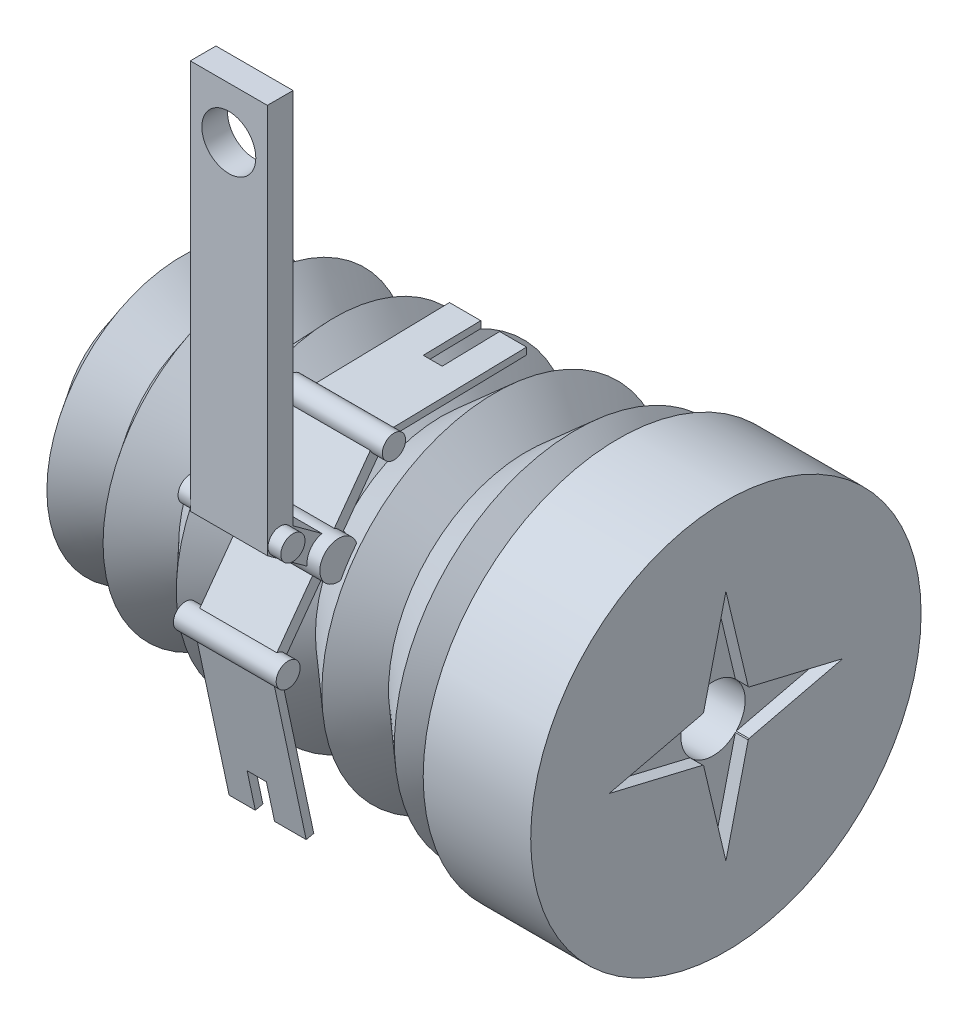
SolidWorks part; units mm, degrees
ref_plane "Ebene vorne" through (0, 0, 0) normal (0, 0, 1) x (1, 0, 0)
ref_plane "Ebene oben" through (0, 0, 0) normal (0, 1, 0) x (1, 0, 0)
ref_plane "Ebene rechts" through (0, 0, 0) normal (1, 0, 0) x (0, 0, -1)
sketch "Skizze2" plane through (0, 0, 0) normal (0, 0, 1) x (1, 0, 0)
  line L0 (0, 0) -> (40, 0) construction
  line L1 (0, 0) -> (0, 6)
  line L2 (40, 0) -> (0, 0)
  line L3 (0, 6) -> (3.3665, 10.5283)
  line L4 (3.3665, 10.5283) -> (6.4121, 8.2642)
  line L5 (6.4121, 8.2642) -> (9.1304, 11.9207)
  line L6 (9.1304, 11.9207) -> (12.157, 9.0646)
  line L7 (12.157, 9.0646) -> (15.1906, 12.2794)
  line L8 (15.1906, 12.2794) -> (17.3749, 9.8003)
  line L9 (17.3749, 9.8003) -> (20.8454, 12.8582)
  line L10 (20.8454, 12.8582) -> (23.5398, 9.8003)
  line L11 (23.5398, 9.8003) -> (27.7236, 13.4867)
  line L12 (27.7236, 13.4867) -> (30.1561, 10.726)
  line L13 (30.1561, 10.726) -> (34.0133, 14.1246)
  line L14 (34.0133, 14.1246) -> (36.4763, 11.3293)
  line L15 (36.4763, 11.3293) -> (37.3235, 15.1947)
  line L16 (37.3235, 15.1947) -> (45.6933, 15.1947)
  line L17 (45.6933, 15.1947) -> (45.6933, 0)
  line L18 (45.6933, 0) -> (40, 0)
  dimension "D1" = 40
  dimension "D2" = 12
revolve "Rotation5" add sketch "Skizze2" angle 360 about L18
sketch "Skizze3" plane through (0, 0, 0) normal (-1, 0, 0) x (0, 0, 1)
  circle A0 centre (0, 0) radius 4.65
  dimension "D1" = 9.3
extrude "Schnitt-Linear austragen1" cut sketch "Skizze3" against normal blind 23
sketch "Skizze4" plane through (23, 0, 0) normal (-1, 0, 0) x (0, 0, 1)
  circle A0 centre (0, 0) radius 2.5
  dimension "D1" = 5
extrude "Schnitt-Linear austragen2" cut sketch "Skizze4" against normal through all
ref_plane "Ebene1" through (20, 0, 0) normal (-1, 0, 0) x (0, 0, 1)
sketch "Skizze8" plane through (20, 0, 0) normal (-1, 0, 0) x (0, 0, 1)
  line L0 (5.1354, 1.7132) -> (16, 9.638)
  line L1 (16, 9.638) -> (16, 40)
  line L2 (16, 40) -> (14, 40)
  line L3 (14, 40) -> (14, 10.6547)
  line L4 (14, 10.6547) -> (3.9568, 3.329)
  line L5 (3.9568, 3.329) -> (5.1354, 1.7132)
  point P2 (0, 0)
  dimension "D1" = 2
  dimension "D2" = 2
  dimension "D3" = 14
  dimension "D4" = 40
extrude "Aufsatz-Linear austragen2" add sketch "Skizze8" against normal blind 6
ref_point "Punkt1"
sketch "Skizze10" plane through (0, 0, 16) normal (0, 0, 1) x (1, 0, 0)
  line L0 (23, 9.638) -> (23, 40) construction
  line L1 (26, 9.638) -> (20, 9.638) construction
  line L2 (26, 40) -> (20, 40) construction
  circle A0 centre (23, 36) radius 2.1
  dimension "D1" = 4
  dimension "D2" = 4.2
extrude "Schnitt-Linear austragen4" cut sketch "Skizze10" against normal blind 6 contours A0
sketch "Skizze13" plane through (0, -1.3267, 0.9677) normal (0, -0.8079, 0.5893) x (1, 0, 0)
  line L0 (20, 12.0015) -> (20, 18.6063) construction
  line L1 (20, 13.9376) -> (26, 13.9376)
  line L2 (20, 13.9376) -> (20, 13.0317)
  line L3 (20, 13.0317) -> (26, 13.0317)
  line L4 (26, 13.9376) -> (26, 13.0317)
  line L5 (26, 11.8549) -> (26, 18.6063) construction
extrude "Aufsatz-Linear austragen3" add sketch "Skizze13" along normal blind 6
sketch "Skizze14" plane through (0, 0.2891, -0.2109) normal (0, 0.8079, -0.5893) x (1, 0, 0)
  line L0 (20, -17.5896) -> (20, -12.108) construction
  line L1 (20, -13.0637) -> (26, -13.0637)
  line L2 (20, -13.0637) -> (20, -13.9504)
  line L3 (20, -13.9504) -> (26, -13.9504)
  line L4 (26, -13.0637) -> (26, -13.9504)
  line L5 (26, -17.5896) -> (26, -11.9627) construction
extrude "Aufsatz-Linear austragen4" add sketch "Skizze14" along normal blind 6
ref_plane "Ebene4" through (26, 12.835, 6.8076) normal (0, -0.5893, -0.8079) x (-1, 0, 0)
sketch "Skizze16" plane through (26, 0, 0) normal (1, 0, 0) x (0, 0, -1)
  line L0 (-15.764, 2.0392) -> (-12.9775, -11.0108)
  line L1 (-15.0321, 1.5054) -> (-15.764, 2.0392) construction
  line L2 (-15.0321, 1.5054) -> (-12.3866, -10.8847)
  line L3 (-12.9775, -11.0108) -> (-12.3866, -10.8847)
  line L4 (-15.764, 2.0392) -> (-15.0321, 1.5054)
extrude "Aufsatz-Linear austragen5" add sketch "Skizze16" against normal blind 6
sketch "Skizze17" plane through (26, 0, 0) normal (1, 0, 0) x (0, 0, -1)
  line L0 (-6.8076, 12.835) -> (4.1747, 13.0793)
  line L1 (-7.5241, 13.3576) -> (4.1747, 13.6178)
  line L2 (4.1747, 13.6178) -> (4.1747, 13.0793)
  line L3 (-7.5241, 13.3576) -> (-6.8076, 12.835)
extrude "Aufsatz-Linear austragen6" add sketch "Skizze17" against normal blind 6
sketch "Skizze19" plane through (45.6933, 0, 0) normal (1, 0, 0) x (0, 0, -1)
  line L0 (-1.7995, 1.7355) -> (-9.0916, 0)
  line L1 (-9.0916, 0) -> (-1.7995, -1.7355)
  line L2 (-1.7995, -1.7355) -> (-2.1584, -1.2615)
  line L3 (-2.1584, -1.2615) -> (-2.4159, -0.6431)
  line L4 (-2.4159, -0.6431) -> (-2.5, 0)
  line L5 (-2.5, 0) -> (-2.4086, 0.6699)
  line L6 (-2.4086, 0.6699) -> (-2.1584, 1.2615)
  line L7 (-2.1584, 1.2615) -> (-1.7995, 1.7355)
  circle A0 centre (0, 0) radius 2.5 construction
extrude "Schnitt-Linear austragen5" cut sketch "Skizze19" against normal blind 1
pattern_circular "Kreismuster1" count 4 every 90 about axis through (0, 0, 0) along (1, 0, 0) of "Schnitt-Linear austragen5"
ref_plane "Ebene5" through (26, 6.8867, 12.2281) normal (-1, 0, 0) x (0, 0, 1)
sketch "Skizze24" plane through (20, 0, 0) normal (-1, 0, 0) x (0, 0, 1)
  circle A0 centre (11.4535, 7.5754) radius 1.4626
extrude "Aufsatz-Linear austragen7" add sketch "Skizze24" against normal blind 7 and the other way blind 1
sketch "Skizze25" plane through (20, 0, 0) normal (-1, 0, 0) x (0, 0, 1)
  circle A0 centre (15.0101, 10.19) radius 0.9418
extrude "Aufsatz-Linear austragen8" add sketch "Skizze25" against normal blind 7 and the other way blind 1
sketch "Skizze26" plane through (26, 0, 0) normal (1, 0, 0) x (0, 0, -1)
  circle A0 centre (-7.1446, 13.07) radius 0.9042
extrude "Aufsatz-Linear austragen9" add sketch "Skizze26" against normal blind 7 and the other way blind 1
sketch "Skizze27" plane through (20, 0, 0) normal (-1, 0, 0) x (0, 0, 1)
  circle A0 centre (15.3814, 1.8039) radius 0.9325
extrude "Aufsatz-Linear austragen10" add sketch "Skizze27" against normal blind 7 and the other way blind 1
sketch "Skizze28" plane through (0, -3.1302, 14.6602) normal (0, -0.2088, 0.978) x (1, 0, 0)
  line L0 (20, -8.0583) -> (26, -8.0583) construction
  line L1 (23.5398, -8.0583) -> (22.0403, -8.0583)
  line L2 (23.5398, -8.0583) -> (23.5398, -5.0063)
  line L3 (23.5398, -5.0063) -> (22.0403, -5.0063)
  line L4 (22.0403, -8.0583) -> (22.0403, -5.0063)
  line L5 (23.5398, -9.8003) -> (23.5398, 9.8003) construction
extrude "Schnitt-Linear austragen6" cut sketch "Skizze28" against normal blind 2
sketch "Skizze29" plane through (0, 13.5183, 0.3007) normal (0, 0.9998, 0.0222) x (1, 0, 0)
  line L0 (20, 4.4765) -> (26, 4.4765) construction
  line L1 (23.9087, 4.4765) -> (22.4365, 4.4765)
  line L2 (23.9087, 4.4765) -> (23.9087, 0)
  line L3 (23.9087, 0) -> (22.4365, 0)
  line L4 (22.4365, 4.4765) -> (22.4365, 0)
extrude "Schnitt-Linear austragen7" cut sketch "Skizze29" against normal blind 0.6
